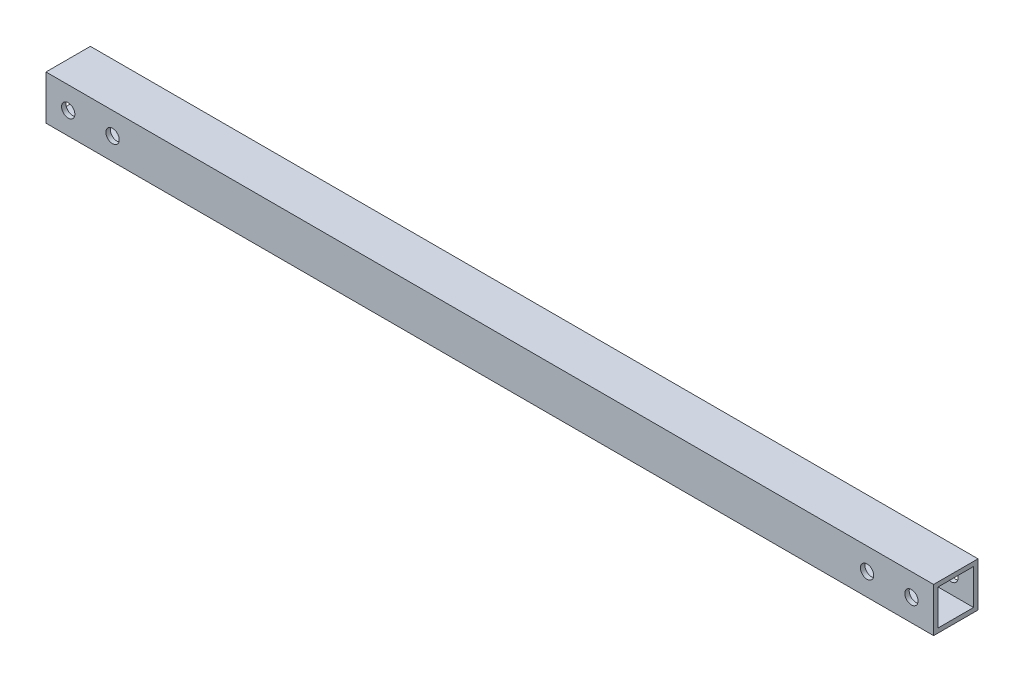
SolidWorks part; units mm, degrees
material "1060 Alloy"
ref_plane "Front Plane" through (0, 0, 0) normal (0, 0, 1) x (1, 0, 0)
ref_plane "Top Plane" through (0, 0, 0) normal (0, 1, 0) x (1, 0, 0)
ref_plane "Right Plane" through (0, 0, 0) normal (1, 0, 0) x (0, 0, -1)
sketch "Sketch1" plane through (0, 0, 0) normal (1, 0, 0) x (0, 0, -1)
  line L0 (8, 8) -> (-8, 8)
  line L1 (-8, 8) -> (-8, -8)
  line L2 (0, 0) -> (0, 27.1676) construction
  line L3 (0, 0) -> (-28.5263, 0) construction
  line L4 (8, 8) -> (8, -8)
  line L5 (8, -8) -> (-8, -8)
  line L7 (-10, 10) -> (10, 10)
  line L8 (-10, 10) -> (-10, -10)
  line L9 (-10, -10) -> (10, -10)
  line L10 (10, 10) -> (10, -10)
  point P8 (0, 8)
  point P11 (8, 0)
  point P12 (-8, 0)
  dimension "D1" = 16
  dimension "D2" = 20
  dimension "D3" = 10
  dimension "D4" = 10
extrude "Boss-Extrude1" add sketch "Sketch1" along normal mid plane 400
sketch "Sketch2" plane through (0, 0, 10) normal (0, 0, 1) x (1, 0, 0)
  line L0 (200, 10) -> (200, -10) construction
  line L1 (0, 0) -> (235.8213, 0) construction
  line L2 (-200, 10) -> (-200, -10) construction
  circle A0 centre (190, 0) radius 3
  circle A1 centre (170, 0) radius 3
  circle A2 centre (-170, 0) radius 3
  circle A3 centre (-190, 0) radius 3
  dimension "D1" = 6
  dimension "D2" = 20
  dimension "D3" = 10
  dimension "D4" = 20
  dimension "D5" = 10
extrude "Cut-Extrude1" cut sketch "Sketch2" against normal through all
